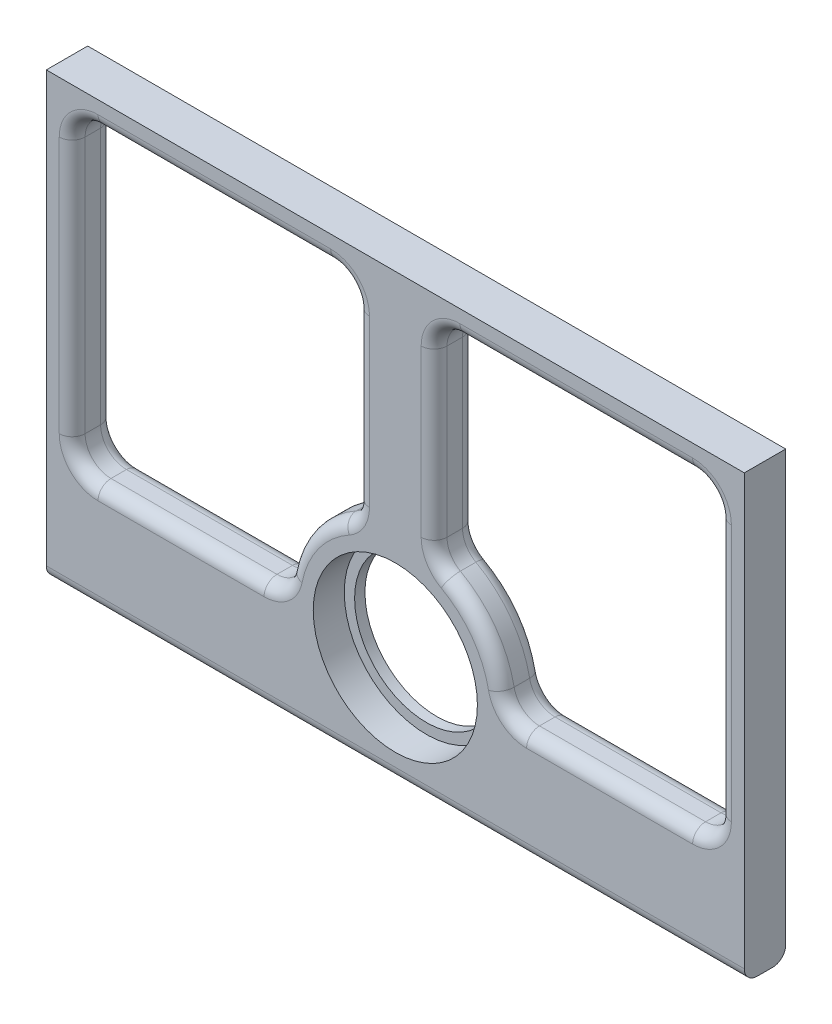
SolidWorks part; units mm, degrees
ref_plane "Front Plane" through (0, 0, 0) normal (0, 0, 1) x (1, 0, 0)
ref_plane "Top Plane" through (0, 0, 0) normal (0, 1, 0) x (1, 0, 0)
ref_plane "Right Plane" through (0, 0, 0) normal (1, 0, 0) x (0, 0, -1)
sketch "Sketch1" plane through (0, 0, 0) normal (0, 0, 1) x (1, 0, 0)
  circle A0 centre (0, 0) radius 31.75
  circle A1 centre (0, 0) radius 41.75
  dimension "D1" = 63.5
  dimension "D2" = 10
extrude "Bearing holder" add sketch "Sketch1" along normal blind 16
sketch "Sketch2" plane through (0, 0, 0) normal (0, 0, -1) x (-1, 0, 0)
  circle A0 centre (0, 0) radius 31.75 construction
  circle A1 centre (0, 0) radius 31.75
  circle A2 centre (0, 0) radius 27.75
  dimension "D1" = 4
extrude "Bearing lip" add sketch "Sketch2" against normal blind 4
sketch "Sketch3" plane through (0, 0, 16) normal (0, 0, 1) x (1, 0, 0)
  line L0 (-135, -41.75) -> (-125, -41.75)
  line L1 (-125, 0) -> (-125, 119.38)
  line L2 (-125, 119.38) -> (-15, 119.38)
  line L3 (125, 119.38) -> (125, 0)
  line L4 (125, -41.75) -> (135, -41.75)
  line L5 (135, -41.75) -> (135, 129.38)
  line L6 (135, 129.38) -> (-135, 129.38)
  line L7 (-135, 129.38) -> (-135, -41.75)
  line L8 (-41.75, -41.75) -> (-125, -41.75)
  line L9 (41.75, -41.75) -> (125, -41.75)
  line L10 (41.75, 0) -> (125, 0)
  line L11 (-41.75, 0) -> (-125, 0)
  line L12 (-15, 119.38) -> (-15, 38.9623)
  line L13 (15, 119.38) -> (15, 38.9623)
  line L14 (15, 119.38) -> (125, 119.38)
  line L17 (-41.75, 0) -> (-36.75, 0)
  line L18 (36.75, 0) -> (41.75, 0)
  line L19 (41.75, -41.75) -> (-41.75, -41.75)
  circle A0 centre (0, 0) radius 41.75 construction
  arc A2 (15, 38.9623) -> (-15, 38.9623) centre (0, 0) ccw
  circle A5 centre (0, 0) radius 36.75
  arc A6 (-36.75, 0) -> (36.75, 0) centre (0, 0) ccw
  point P23 (0, 0)
  point P25 (0, 0)
  dimension "D1" = 10
  dimension "D2" = 10
  dimension "D3" = 10
  dimension "D4" = 270
  dimension "D5" = 129.38
  dimension "D6" = 15
  dimension "D7" = 30
  dimension "D8" = 135
  dimension "D9" = 5
extrude "Box adapter" add sketch "Sketch3" against normal blind 16
fillet "Structural fillets" radius 10 10 edges at (41.75, 0, 8) (15, 38.9623, 8) (-41.75, 0, 8) (-15, 38.9623, 8) (-125, 0, 8) (125, 0, 8) (-15, 119.38, 8) (125, 119.38, 8) (15, 119.38, 8) (-125, 119.38, 8)
fillet "Smaller fillets" radius 5 42 edges at (-17.9289, 116.4511, 0) (-17.9289, 116.4511, 16) (-15, 77.3454, 0) (-15, 77.3454, 16) (-16.3887, 40.2269, 0) (-16.3887, 40.2269, 16) (-33.7219, 24.6149, 0) (-33.7219, 24.6149, 16) (-44.4234, 2.2759, 16) (-44.4234, 2.2759, 0) (-82.8873, 0, 16) (-82.8873, 0, 0) (-122.0711, 2.9289, 0) (-122.0711, 2.9289, 16) (-125, 59.69, 16) (-125, 59.69, 0) (-122.0711, 116.4511, 0) (-122.0711, 116.4511, 16) (122.0711, 116.4511, 0) (122.0711, 116.4511, 16) (125, 59.69, 0) (125, 59.69, 16) (122.0711, 2.9289, 0) (122.0711, 2.9289, 16) (82.8873, 0, 0) (82.8873, 0, 16) (44.4234, 2.2759, 0) (44.4234, 2.2759, 16) (33.7219, 24.6149, 16) (33.7219, 24.6149, 0) (16.3887, 40.2269, 0) (16.3887, 40.2269, 16) (15, 77.3454, 16) (15, 77.3454, 0) (17.9289, 116.4511, 0) (17.9289, 116.4511, 16) (0, -41.75, 0) (0, -41.75, 16) (-70, 119.38, 0) (-70, 119.38, 16) (70, 119.38, 0) (70, 119.38, 16)
